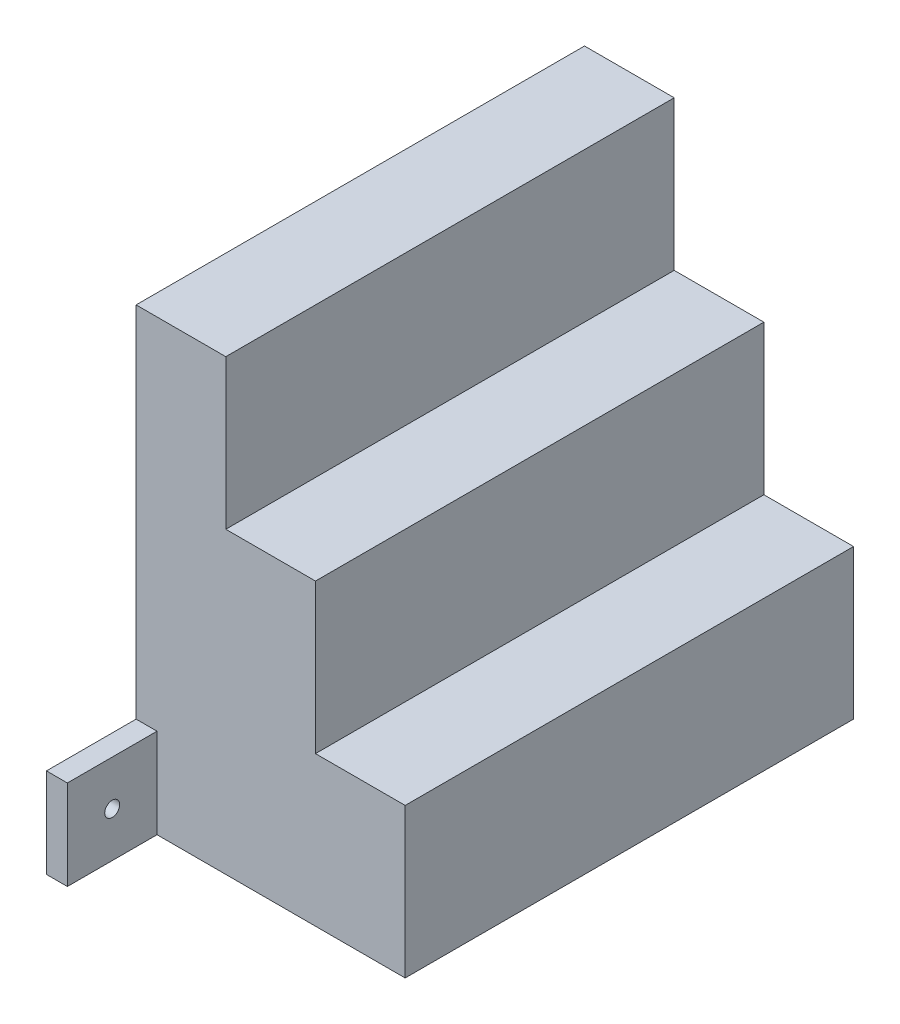
SolidWorks part; units mm, degrees
material "1060 Alloy"
ref_plane "Front Plane" through (0, 0, 0) normal (0, 0, 1) x (1, 0, 0)
ref_plane "Top Plane" through (0, 0, 0) normal (0, 1, 0) x (1, 0, 0)
ref_plane "Right Plane" through (0, 0, 0) normal (1, 0, 0) x (0, 0, -1)
sketch "Sketch1" plane through (0, 0, 0) normal (0, 0, 1) x (1, 0, 0)
  line L0 (0, 0) -> (0, 381)
  line L1 (0, 381) -> (76.2, 381)
  line L2 (76.2, 381) -> (76.2, 254)
  line L3 (76.2, 254) -> (152.4, 254)
  line L4 (152.4, 254) -> (152.4, 127)
  line L5 (152.4, 127) -> (228.6, 127)
  line L6 (228.6, 127) -> (228.6, 0)
  line L7 (228.6, 0) -> (0, 0)
  dimension "D1" = 76.2
  dimension "D2" = 127
extrude "Boss-Extrude1" add sketch "Sketch1" along normal mid plane 381
sketch "Sketch2" plane through (0, 0, 0) normal (-1, 0, 0) x (0, 0, 1)
  line L0 (-190.5, 381) -> (-190.5, 0) construction
  line L1 (190.5, 0) -> (266.7, 0)
  line L2 (190.5, 0) -> (190.5, 76.2)
  line L3 (190.5, 76.2) -> (266.7, 76.2)
  line L4 (266.7, 0) -> (266.7, 76.2)
  line L5 (190.5, 0) -> (-190.5, 0) construction
  line L6 (-266.7, 0) -> (-190.5, 0)
  line L7 (-266.7, 76.2) -> (-190.5, 76.2)
  line L8 (-190.5, 0) -> (-190.5, 76.2)
  line L9 (-266.7, 0) -> (-266.7, 76.2)
  circle A0 centre (228.6, 38.1) radius 6.35
  circle A1 centre (-228.6, 38.1) radius 6.35
  dimension "D2" = 12.7
  dimension "D6" = 38.1
  dimension "D1" = 457.2
  dimension "D4" = 419.1
  dimension "D5" = 38.1
extrude "Boss-Extrude2" add sketch "Sketch2" against normal blind 17.78
